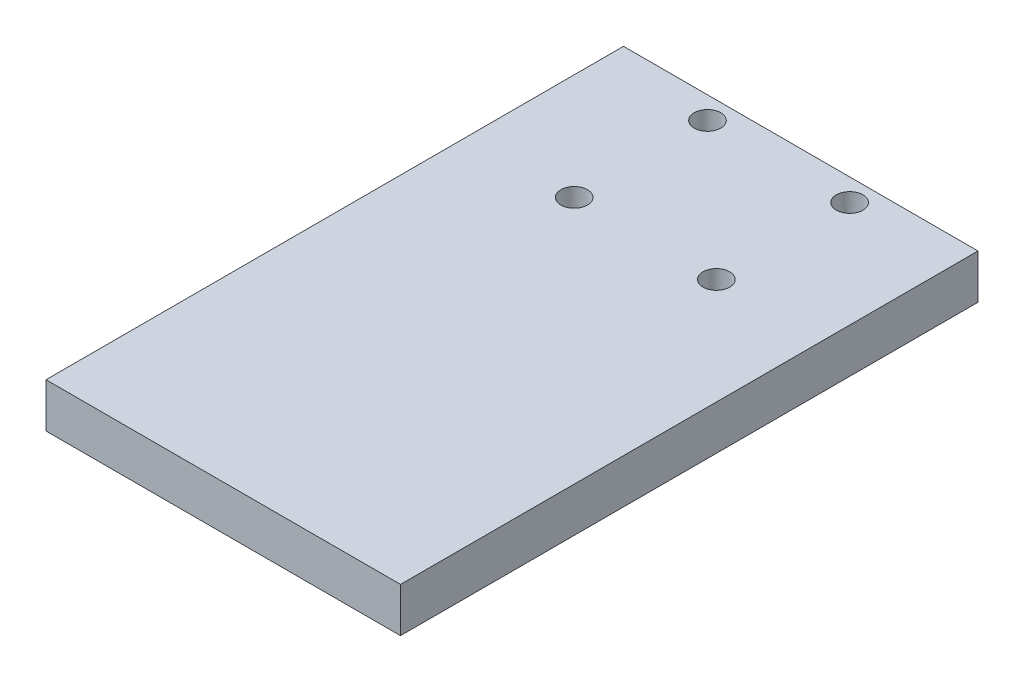
SolidWorks part; units mm, degrees
ref_plane "前视基准面" through (0, 0, 0) normal (0, 0, 1) x (1, 0, 0)
ref_plane "上视基准面" through (0, 0, 0) normal (0, 1, 0) x (1, 0, 0)
ref_plane "右视基准面" through (0, 0, 0) normal (1, 0, 0) x (0, 0, -1)
other "Configuration Table"
sketch "草图1" plane through (0, 0, 0) normal (0, 1, 0) x (1, 0, 0)
  line L1 (0, 0) -> (-39.9, 0)
  line L2 (0, 0) -> (0, 20)
  line L3 (0, 20) -> (-39.9, 20)
  line L4 (-39.9, 0) -> (-39.9, 20)
  dimension "D1" = 39.9
  dimension "D2" = 20
extrude "凸台-拉伸1" add sketch "草图1" along normal blind 5
sketch "草图2" plane through (0, 5, 0) normal (0, 1, 0) x (1, 0, 0)
  line L0 (-19.95, 20) -> (-19.95, 17.5) construction
  line L1 (0, 20) -> (-39.9, 20) construction
  line L2 (-19.95, 17.5) -> (-27.95, 17.5) construction
  line L3 (-19.95, 17.5) -> (-11.95, 17.5) construction
  line L4 (-39.9, 10) -> (-38.7367, 10) construction
  line L5 (-39.9, 20) -> (-39.9, 0) construction
  line L6 (-19.95, 2.5) -> (-11.95, 2.5) construction
  line L7 (-19.95, 2.5) -> (-27.95, 2.5) construction
  line L8 (-19.95, 0) -> (-19.95, 2.5) construction
  circle A0 centre (-27.95, 17.5) radius 1.5
  circle A1 centre (-11.95, 17.5) radius 1.5
  circle A2 centre (-11.95, 2.5) radius 1.5
  circle A3 centre (-27.95, 2.5) radius 1.5
  dimension "D4" = 3
  dimension "D5" = 3
  dimension "D1" = 2.5
  dimension "D2" = 8
  dimension "D3" = 8
extrude "切除-拉伸1" cut sketch "草图2" against normal blind 5
sketch "草图4" plane through (0, 0, 0) normal (0, 0, 1) x (1, 0, 0)
  line L4 (-39.9, 0) -> (0, 0)
  line L5 (0, 0) -> (0, 5)
  line L6 (0, 5) -> (-39.9, 5)
  line L7 (-39.9, 5) -> (-39.9, 0)
  line L8 (-39.9, 0) -> (0, 0)
  line L9 (0, 0) -> (0, 5)
  line L10 (0, 5) -> (-39.9, 5)
  line L11 (-39.9, 5) -> (-39.9, 0)
  dimension "D1" = 0
extrude "凸台-拉伸2" add sketch "草图4" along normal blind 45
